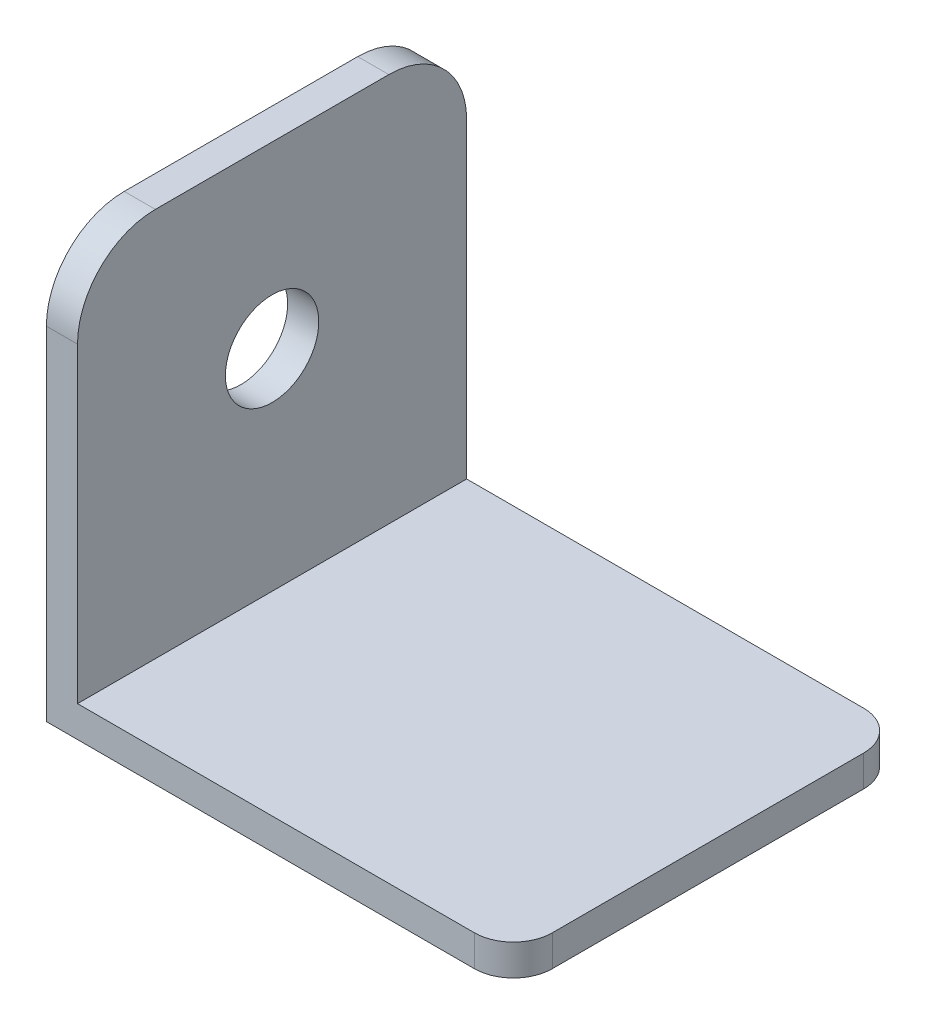
SolidWorks part; units mm, degrees
ref_plane "Front Plane" through (0, 0, 0) normal (0, 0, 1) x (1, 0, 0)
ref_plane "Top Plane" through (0, 0, 0) normal (0, 1, 0) x (1, 0, 0)
ref_plane "Right Plane" through (0, 0, 0) normal (1, 0, 0) x (0, 0, -1)
sketch "Sketch1" plane through (0, 0, 0) normal (0, 1, 0) x (1, 0, 0)
  line L1 (-30, 25) -> (30, 25)
  line L2 (-30, 25) -> (-30, -25)
  line L3 (-30, -25) -> (30, -25)
  line L4 (30, 25) -> (30, -25)
  line L5 (-30, 25) -> (30, -25) construction
  line L6 (-30, -25) -> (30, 25) construction
  point P0 (0, 0)
  dimension "D1" = 60
  dimension "D2" = 50
extrude "Boss-Extrude3" add sketch "Sketch1" along normal blind 4
sketch "Sketch3" plane through (-30, 0, 0) normal (-1, 0, 0) x (0, 0, 1)
  line L0 (-25, 4) -> (25, 4)
  line L1 (0, 4) -> (0, 54) construction
  line L2 (-25, 4) -> (-25, 44)
  line L3 (-15, 54) -> (15, 54)
  line L4 (25, 44) -> (25, 4)
  circle A0 centre (0, 24) radius 18.5 construction
  circle A2 centre (0, 17) radius 3 construction
  circle A3 centre (0, 31) radius 6
  arc A4 (15, 54) -> (25, 44) centre (15, 44) cw
  arc A5 (-25, 44) -> (-15, 54) centre (-15, 44) cw
  dimension "D2" = 37
  dimension "D3" = 6
  dimension "D4" = 7
  dimension "D6" = 12
  dimension "D8" = 10
  dimension "D1" = 50
  dimension "D5" = 20
  dimension "D7" = 7
extrude "Boss-Extrude4" add sketch "Sketch3" against normal blind 4
fillet "Fillet1" radius 5 2 edges at (30, 2, -25) (30, 2, 25)
